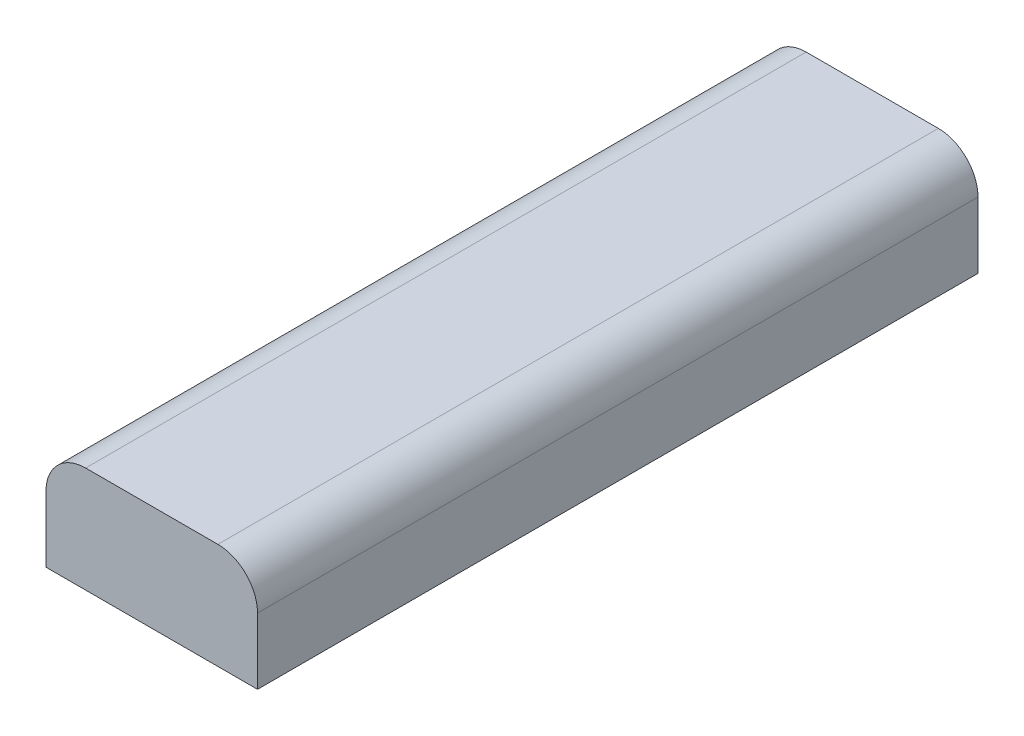
SolidWorks part; units mm, degrees
ref_plane "Спереди" through (0, 0, 0) normal (0, 0, 1) x (1, 0, 0)
ref_plane "Сверху" through (0, 0, 0) normal (0, 1, 0) x (1, 0, 0)
ref_plane "Справа" through (0, 0, 0) normal (1, 0, 0) x (0, 0, -1)
sketch "Эскиз1" plane through (0, 0, 0) normal (0, 0, 1) x (1, 0, 0)
  line L1 (0, 0) -> (32, 0)
  line L2 (0, 0) -> (0, 16)
  line L3 (0, 16) -> (32, 16)
  line L4 (32, 0) -> (32, 16)
  dimension "D1" = 16
  dimension "D2" = 32
extrude "Бобышка-Вытянуть1" add sketch "Эскиз1" along normal blind 109
fillet "Скругление1" radius 6 2 edges at (0, 16, 54.5) (32, 16, 54.5)
